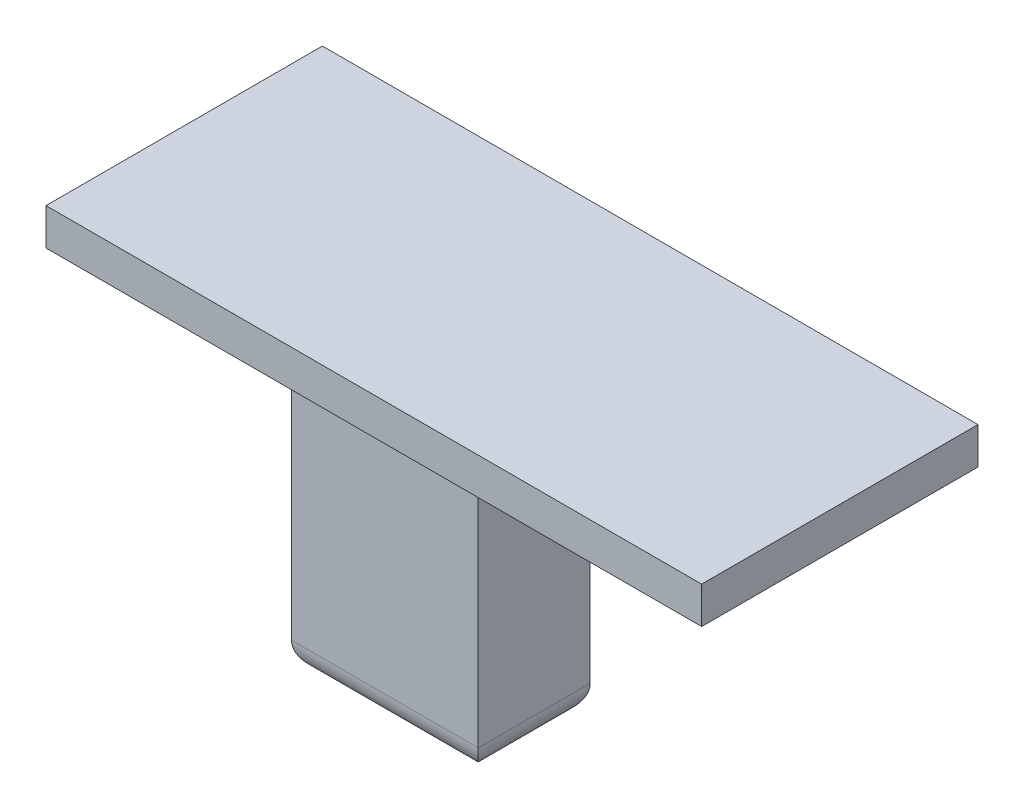
SolidWorks part; units mm, degrees
ref_plane "Front Plane" through (0, 0, 0) normal (0, 0, 1) x (1, 0, 0)
ref_plane "Top Plane" through (0, 0, 0) normal (0, 1, 0) x (1, 0, 0)
ref_plane "Right Plane" through (0, 0, 0) normal (1, 0, 0) x (0, 0, -1)
sketch "Sketch1" plane through (0, 0, 0) normal (0, 1, 0) x (1, 0, 0)
  line L6 (-22.3, 16.05) -> (22.3, 16.05)
  line L7 (-22.3, 16.05) -> (-22.3, -2.75)
  line L8 (-22.3, -2.75) -> (22.3, -2.75)
  line L9 (22.3, 16.05) -> (22.3, -2.75)
  dimension "D1" = 44.6
  dimension "D2" = 22.3
  dimension "D3" = 18.8
  dimension "D4" = 2.75
extrude "Boss-Extrude1" add sketch "Sketch1" against normal blind 2.5
sketch "Sketch2" plane through (0, 0, 0) normal (0, 1, 0) x (1, 0, 0)
  line L1 (6.35, -2) -> (-6.35, -2)
  line L2 (6.35, -2) -> (6.35, 5.62)
  line L3 (6.35, 5.62) -> (-6.35, 5.62)
  line L4 (-6.35, -2) -> (-6.35, 5.62)
  dimension "D1" = 12.7
  dimension "D2" = 7.62
  dimension "D3" = 2
  dimension "D4" = 6.35
extrude "Boss-Extrude2" add sketch "Sketch2" against normal blind 20
fillet "Fillet1" radius 2 4 edges at (0, -20, -5.62) (-6.35, -20, -1.81) (0, -20, 2) (6.35, -20, -1.81)
fillet "Fillet2" radius 0.5 4 edges at (-6.35, -2.5, -1.81) (0, -2.5, 2) (0, -2.5, -5.62) (6.35, -2.5, -1.81)
